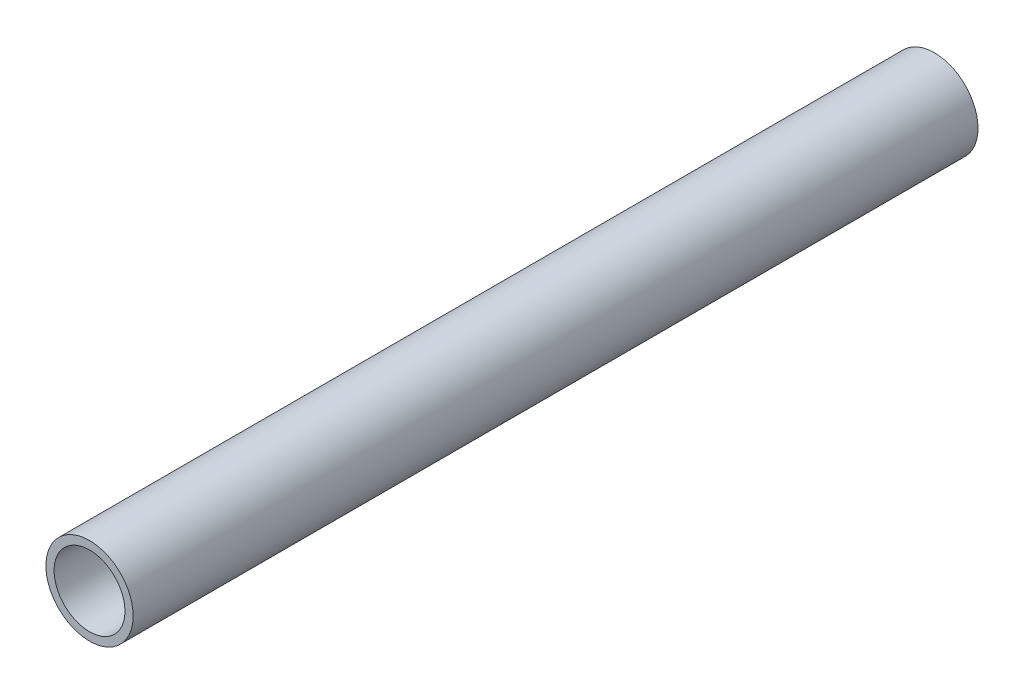
SolidWorks part; units mm, degrees
ref_plane "前视基准面" through (0, 0, 0) normal (0, 0, 1) x (1, 0, 0)
ref_plane "上视基准面" through (0, 0, 0) normal (0, 1, 0) x (1, 0, 0)
ref_plane "右视基准面" through (0, 0, 0) normal (1, 0, 0) x (0, 0, -1)
sketch "草图1" plane through (0, 0, 0) normal (0, 0, 1) x (1, 0, 0)
  circle A0 centre (0, 0) radius 6.5
  circle A1 centre (0, 0) radius 8
extrude "凸台-拉伸1" add sketch "草图1" along normal blind 155
